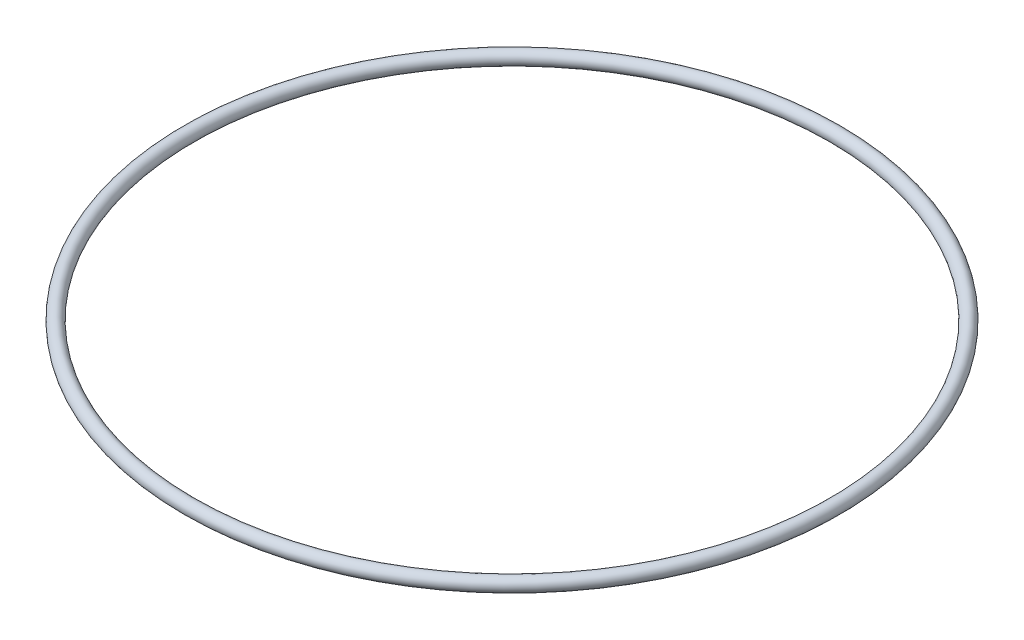
SolidWorks part; units mm, degrees
material "Kauczuk krzemowy"
ref_plane "Płaszczyzna przednia" through (0, 0, 0) normal (0, 0, 1) x (1, 0, 0)
ref_plane "Płaszczyzna górna" through (0, 0, 0) normal (0, 1, 0) x (1, 0, 0)
ref_plane "Płaszczyzna prawa" through (0, 0, 0) normal (1, 0, 0) x (0, 0, -1)
sketch "Szkic1" plane through (0, 0, 0) normal (0, 0, 1) x (1, 0, 0)
  line L0 (1.25, 0) -> (59.5, 0)
  line L1 (59.5, -11.058) -> (59.5, 12.7104)
  circle A0 centre (0, 0) radius 1.25
  circle A1 centre (0, 0) radius 0.6455
revolve "Obrót1" add sketch "Szkic1" angle 360 about L1
